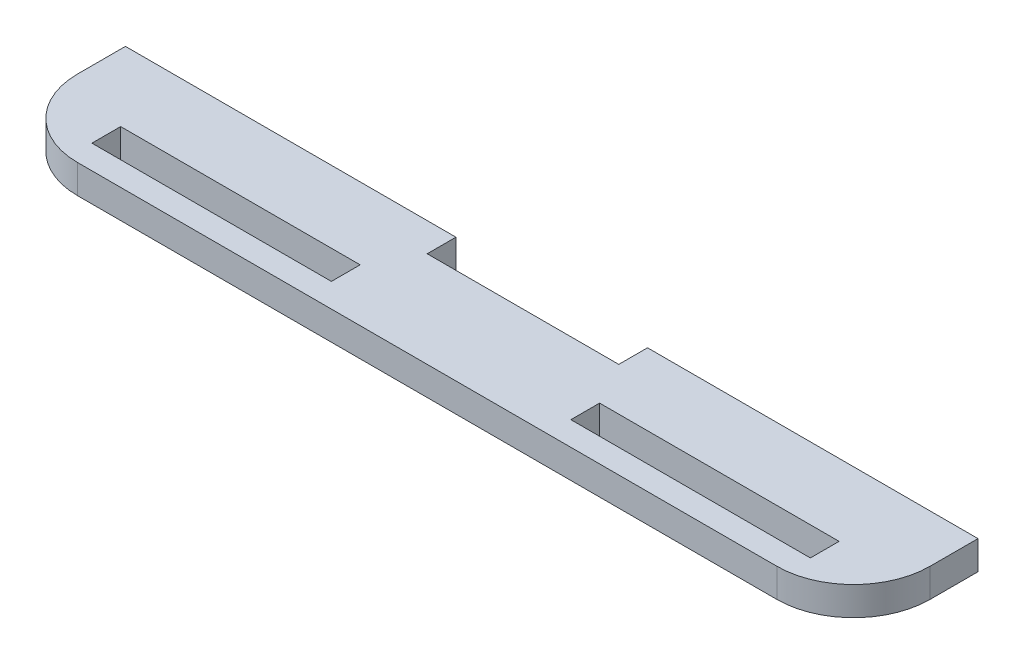
SolidWorks part; units mm, degrees
material "PVC rigido"
ref_plane "Piano frontale" through (0, 0, 0) normal (0, 0, 1) x (1, 0, 0)
ref_plane "Piano superiore" through (0, 0, 0) normal (0, 1, 0) x (1, 0, 0)
ref_plane "Piano destro" through (0, 0, 0) normal (1, 0, 0) x (0, 0, -1)
sketch "Schizzo1" plane through (0, 0, 0) normal (0, 0, 1) x (1, 0, 0)
  line L1 (44.5, 24) -> (-44.5, 24)
  line L2 (44.5, 24) -> (44.5, 21)
  line L3 (44.5, 21) -> (-44.5, 21)
  line L4 (-44.5, 24) -> (-44.5, 21)
extrude "Estrusione-Estrusione1" add sketch "Schizzo1" along normal up to surface (10 mm away) and the other way up to surface (3 mm away)
sketch "Schizzo2" plane through (0, 21, 0) normal (0, -1, 0) x (1, 0, 0)
  line L0 (-37.5, 4.5) -> (-37.5, 7.5) construction
  line L1 (-37.5, 4.5) -> (-12.5, 4.5)
  line L2 (-37.5, 4.5) -> (-37.5, 7.5)
  line L3 (-37.5, 7.5) -> (-12.5, 7.5)
  line L4 (-12.5, 4.5) -> (-12.5, 7.5)
  line L5 (12.5, 4.5) -> (37.5, 4.5)
  line L6 (12.5, 4.5) -> (12.5, 7.5)
  line L7 (12.5, 7.5) -> (37.5, 7.5)
  line L8 (37.5, 4.5) -> (37.5, 7.5)
  line L9 (-37.5, 7.5) -> (-12.5, 7.5) construction
extrude "Taglio-Estrusione1" cut sketch "Schizzo2" against normal blind 10
sketch "Schizzo3" plane through (0, 24, 0) normal (0, 1, 0) x (1, 0, 0)
  line L0 (44.5, 3) -> (-44.5, 3) construction
  line L1 (10, 3) -> (-10, 3)
  line L2 (10, 3) -> (10, 0)
  line L3 (10, 0) -> (-10, 0)
  line L4 (-10, 3) -> (-10, 0)
  line L5 (10, 3) -> (10, 0) construction
extrude "Taglio-Estrusione2" cut sketch "Schizzo3" against normal blind 10
fillet "Raccordo1" radius 8 2 edges at (-44.5, 22.5, 10) (44.5, 22.5, 10)
